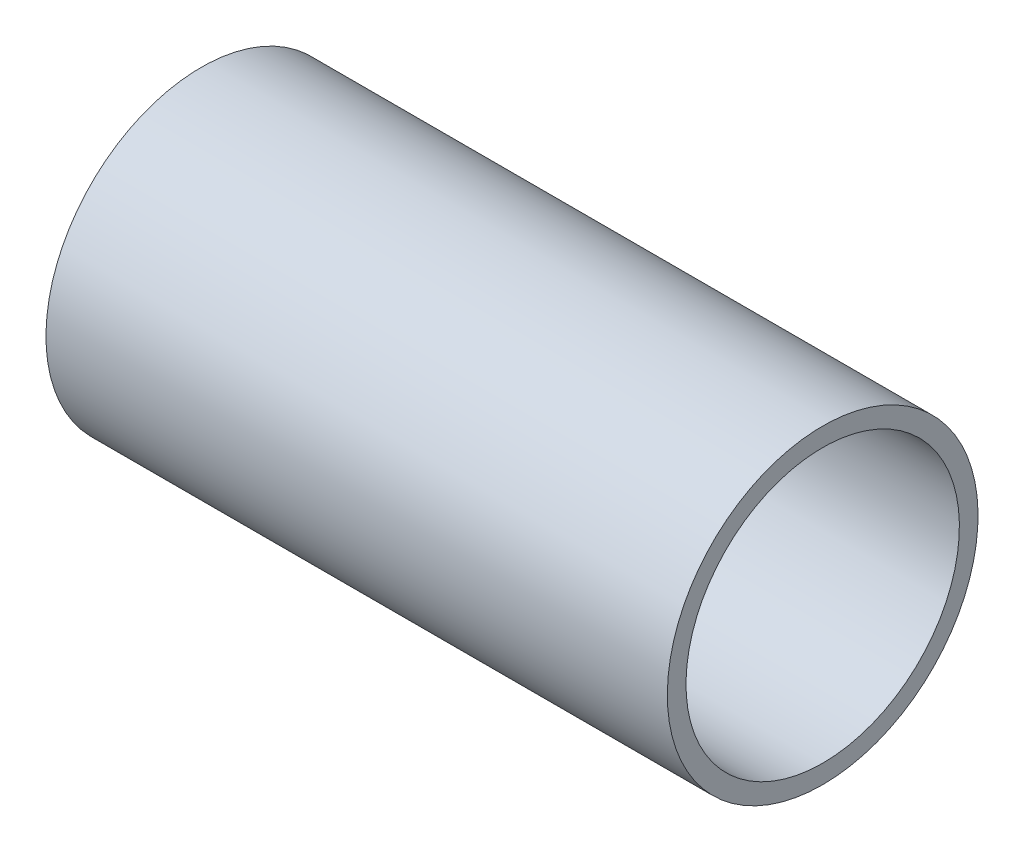
SolidWorks part; units mm, degrees
ref_plane "Front Plane" through (0, 0, 0) normal (0, 0, 1) x (1, 0, 0)
ref_plane "Top Plane" through (0, 0, 0) normal (0, 1, 0) x (1, 0, 0)
ref_plane "Right Plane" through (0, 0, 0) normal (1, 0, 0) x (0, 0, -1)
sketch "Sketch1" plane through (0, 0, 0) normal (0, 0, 1) x (1, 0, 0)
  line L0 (0, 0) -> (100, 0) construction
  line L2 (0, 25) -> (100, 25)
  line L3 (0, 25) -> (0, 22)
  line L4 (0, 22) -> (100, 22)
  line L5 (100, 25) -> (100, 22)
  dimension "D1" = 3
  dimension "L" = 100
  dimension "D" = 50
revolve "Revolve1" add sketch "Sketch1" angle 360 about L0
sketch "Sketch2" [suppressed] plane through (0, 0, 0) normal (0, 0, 1) x (1, 0, 0)
  line L0 (15, 10) -> (15, 7) construction
  line L1 (0, 10) -> (15, 10) construction
  line L2 (0, 10) -> (0, 9.7)
  line L3 (0, 10) -> (0, 7) construction
  line L4 (15, 10) -> (15, 9.7)
  line L5 (0, 9.7) -> (15, 9.7) construction
  line L6 (0, 10) -> (0, 10.3)
  line L7 (0, 10.3) -> (15, 10.3)
  line L8 (15, 10.3) -> (15, 10)
  arc A0 (0, 9.7) -> (15, 9.7) centre (7.5, -83.9) cw
  dimension "D1" = 0.3
revolve "Cut-Revolve1" [suppressed] cut sketch "Sketch2" angle 360 about L0
ref_plane "Plane1" [suppressed] through (0, 10, 0) normal (0, 1, 0) x (1, 0, 0)
hole_wizard "Diameter Hole1" [suppressed] positions "Sketch4" profile "Sketch3" hole size "Ø4.0" standard "JIS"
sketch "Sketch4" [suppressed] plane through (0, 10, 0) normal (0, 1, 0) x (1, 0, 0)
  line L0 (0, 0) -> (15, 0) construction
  point P0 (7.5, 0)
  dimension "D1" = 50
sketch "Sketch3" [suppressed] plane through (7.5, 10, 0) normal (1, 0, 0) x (0, 0, 1)
  line L0 (0, 0) -> (0, 20)
  line L1 (0, 20) -> (2, 20)
  line L2 (2, 20) -> (2, 0)
  line L5 (2, 0) -> (0, 0)
  line L11 (0, 0) -> (0, 20) construction
  dimension "MSM_1" = 4
  dimension "Thru Hole Depth" = 20
pattern_circular "CirPattern1" [suppressed] count 2 over 90
equation "\"Plane dim\"= \"D@Sketch1\" * 0.5"
equation "\"D1@Sketch4\"=\"L@Sketch1\"/2"
